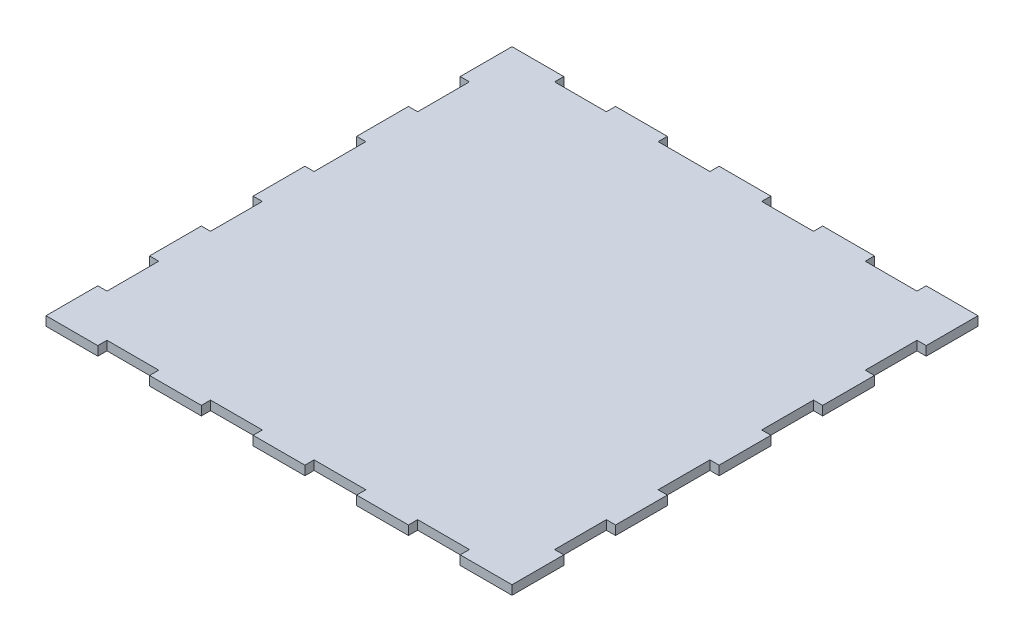
SolidWorks part; units mm, degrees
ref_plane "Front Plane" through (0, 0, 0) normal (0, 0, 1) x (1, 0, 0)
ref_plane "Top Plane" through (0, 0, 0) normal (0, 1, 0) x (1, 0, 0)
ref_plane "Right Plane" through (0, 0, 0) normal (1, 0, 0) x (0, 0, -1)
sketch "Sketch1" plane through (0, 0, 0) normal (0, 1, 0) x (1, 0, 0)
  line L1 (-76, 76) -> (76, 76) construction
  line L2 (-76, 76) -> (-76, -76) construction
  line L3 (-76, -76) -> (76, -76) construction
  line L4 (76, 76) -> (76, -76) construction
  line L5 (0, -76) -> (0, 76) construction
  line L6 (-76, 0) -> (76, 0) construction
  line L8 (-76, -76) -> (-59.1111, -76)
  line L9 (-59.1111, -76) -> (-59.1111, -73)
  line L10 (-59.1111, -73) -> (-42.2222, -73)
  line L11 (-42.2222, -73) -> (-42.2222, -76)
  line L12 (-42.2222, -76) -> (-25.3333, -76)
  line L13 (-25.3333, -76) -> (-25.3333, -73)
  line L14 (-25.3333, -73) -> (-8.4444, -73)
  line L15 (-8.4444, -73) -> (-8.4444, -76)
  line L16 (-8.4444, -76) -> (0, -76)
  line L17 (0, -76) -> (0, 0)
  line L18 (-76, -76) -> (-76, -59.1111)
  line L19 (-76, -59.1111) -> (-73, -59.1111)
  line L20 (-73, -59.1111) -> (-73, -42.2222)
  line L21 (-73, -42.2222) -> (-76, -42.2222)
  line L22 (-76, -42.2222) -> (-76, -25.3333)
  line L23 (-76, -25.3333) -> (-73, -25.3333)
  line L24 (-73, -25.3333) -> (-73, -8.4444)
  line L25 (-73, -8.4444) -> (-76, -8.4444)
  line L26 (-76, -8.4444) -> (-76, 0)
  line L27 (-76, 0) -> (0, 0)
  point P6 (0, 0)
  point P23 (0, 0)
  point P160 (0, 0)
  dimension "D2" = 152
  dimension "D3" = 3
  dimension "D4" = 16.8889
  dimension "D5" = 16.8889
  dimension "D6" = 16.8889
  dimension "D7" = 16.8889
  dimension "D8" = 16.8889
  dimension "D9" = 16.8889
  dimension "D10" = 16.8889
  dimension "D11" = 16.8889
  dimension "D12" = 3
extrude "Boss-Extrude1" add sketch "Sketch1" along normal blind 3
mirror "Mirror1" about plane through (0, 0, 0) normal (0, 0, 1) of "Boss-Extrude1"
equation "\"D5@Sketch1\"=\"D4@Sketch1\""
equation "\"D6@Sketch1\"=\"D4@Sketch1\""
equation "\"D7@Sketch1\"=\"D4@Sketch1\""
equation "\"D8@Sketch1\"=\"D4@Sketch1\""
equation "\"D9@Sketch1\"=\"D4@Sketch1\""
equation "\"D10@Sketch1\"=\"D4@Sketch1\""
equation "\"D11@Sketch1\"=\"D4@Sketch1\""
equation "\"D12@Sketch1\"=\"D3@Sketch1\""
